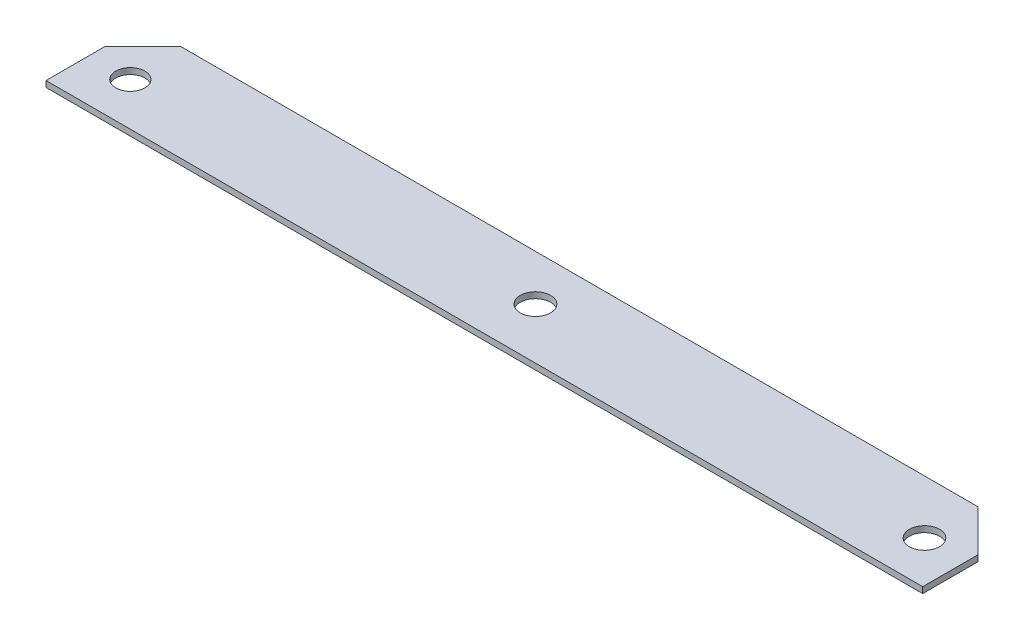
SolidWorks part; units mm, degrees
ref_plane "Front" through (0, 0, 0) normal (0, 0, 1) x (1, 0, 0)
ref_plane "Top" through (0, 0, 0) normal (0, 1, 0) x (1, 0, 0)
ref_plane "Right" through (0, 0, 0) normal (1, 0, 0) x (0, 0, -1)
sketch "Sketch1" plane through (0, 0, 0) normal (0, 1, 0) x (1, 0, 0)
  line L0 (0, 15.5215) -> (9.8785, 25.4)
  line L1 (0, 0) -> (230, 0)
  line L2 (0, 0) -> (0, 25.4)
  line L3 (0, 25.4) -> (230, 25.4)
  line L4 (230, 0) -> (230, 25.4)
  line L5 (219.11, 25.4) -> (230, 14.51)
  circle A0 centre (1.8963, 23.827) radius 1.0969
  circle A1 centre (10.8273, 11.2956) radius 3.825
  circle A2 centre (115, 13.4) radius 3.9795
  circle A3 centre (219.1727, 11.2956) radius 3.9601
  dimension "D1" = 230
  dimension "D2" = 25.4
  dimension "D3" = 12
  dimension "D4" = 115
extrude "Boss-Extrude1" add sketch "Sketch1" along normal blind 1.5875 contours L5 L3 L0 L2 L1 L4
